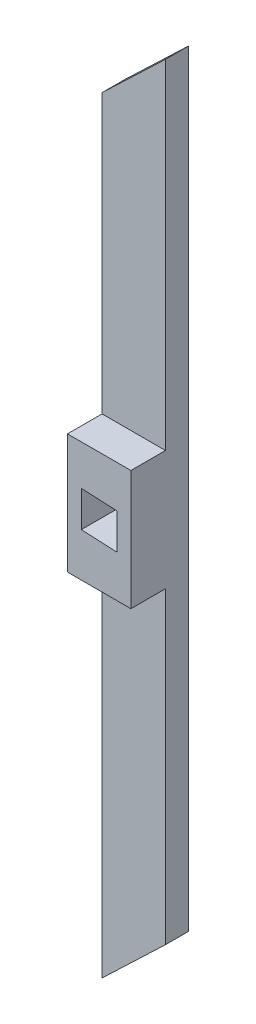
SolidWorks part; units mm, degrees
ref_plane "Plan de face" through (0, 0, 0) normal (0, 0, 1) x (1, 0, 0)
ref_plane "Plan de dessus" through (0, 0, 0) normal (0, 1, 0) x (1, 0, 0)
ref_plane "Plan de droite" through (0, 0, 0) normal (1, 0, 0) x (0, 0, -1)
sketch "Esquisse2" plane through (0, 0, 0) normal (0, 0, 1) x (1, 0, 0)
  line L0 (11, 6.5) -> (11, 75)
  line L1 (0, 0) -> (11, 0)
  line L2 (0, 0) -> (0, 6.5)
  line L3 (0, 6.5) -> (11, 6.5)
  line L4 (11, 0) -> (11, 6.5)
  line L5 (0, 64.5) -> (0, 6.5)
  line L6 (11, 75) -> (0, 64.5)
  line L7 (0, 0) -> (0, -68.5)
  line L8 (11, 0) -> (11, -58)
  line L9 (11, -58) -> (0, -68.5)
  dimension "D1" = 11
  dimension "D2" = 6.5
  dimension "D3" = 68.5
  dimension "D4" = 68.5
  dimension "D5" = 58
  dimension "D6" = 58
extrude "Boss.-Extru.2" add sketch "Esquisse2" along normal blind 10 contours L9 L8 L1 L7 | L0 L6 L5 L3
sketch "Esquisse4" plane through (0, 0, 10) normal (0, 0, 1) x (1, 0, 0)
  line L0 (2.4073, 3.0566) -> (2.4073, 9.2566)
  line L1 (2.4073, 9.2566) -> (8.6, 8.9566)
  line L2 (11, 75) -> (11, -58) construction
  line L3 (8.6, 8.9566) -> (8.6, 2.7566)
  line L4 (8.6, 2.7566) -> (2.4073, 3.0566)
  dimension "D1" = 6.2
  dimension "D2" = 6.2
  dimension "D3" = 6.2
  dimension "D4" = 6.2
  dimension "D5" = 2.4
extrude "Enlèv. mat.-Extru.25" cut sketch "Esquisse4" against normal blind 7
sketch "Esquisse5" plane through (0, 0, 10) normal (0, 0, 1) x (1, 0, 0)
  line L0 (8.6, 8.9566) -> (2.4073, 9.2566) construction
  line L1 (-15.4156, 16.2386) -> (22.183, 16.2386)
  line L2 (-15.4156, 16.2386) -> (-15.4156, 84.7658)
  line L3 (-15.4156, 84.7658) -> (22.183, 84.7658)
  line L4 (22.183, 16.2386) -> (22.183, 84.7658)
  line L5 (8.6, 5.8566) -> (39.4519, 5.8566) construction
  line L6 (8.6, 2.7566) -> (8.6, 8.9566) construction
  line L7 (22.183, -4.5255) -> (22.183, -73.0527)
  line L8 (-15.4156, -73.0527) -> (22.183, -73.0527)
  line L9 (-15.4156, -4.5255) -> (-15.4156, -73.0527)
  line L10 (-15.4156, -4.5255) -> (22.183, -4.5255)
  point P14 (22.183, -73.0527)
  dimension "D1" = 6.982
extrude "Enlèv. mat.-Extru.26" cut sketch "Esquisse5" against normal blind 6
